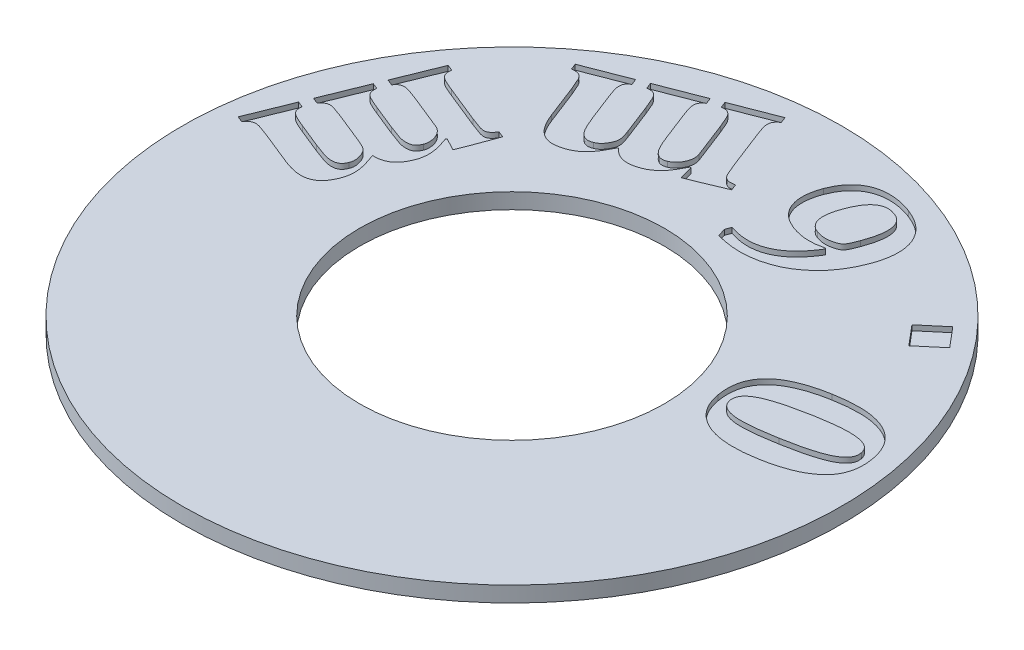
SolidWorks part; units mm, degrees
ref_plane "Front Plane" through (0, 0, 0) normal (0, 0, 1) x (1, 0, 0)
ref_plane "Top Plane" through (0, 0, 0) normal (0, 1, 0) x (1, 0, 0)
ref_plane "Right Plane" through (0, 0, 0) normal (1, 0, 0) x (0, 0, -1)
sketch "Sketch1" plane through (0, 0, 0) normal (0, 1, 0) x (1, 0, 0)
  circle A0 centre (0, 0) radius 12.7
  dimension "D1" = 25.4
extrude "Boss-Extrude1" add sketch "Sketch1" along normal blind 0.6
sketch "Sketch2" plane through (0, 0, 0) normal (0, -1, 0) x (-1, 0, 0)
  circle A0 centre (0, 0) radius 5.8674
  dimension "D1" = 11.7348
extrude "Cut-Extrude1" cut sketch "Sketch2" against normal through all
sketch "Sketch4" plane through (0, 0.6, 0) normal (0, 1, 0) x (1, 0, 0)
  circle A0 centre (0, 0) radius 12.0429 construction
  text T0 "<b>0.6mm</b>" font "Cambria" height 5.08
extrude "Cut-Extrude2" cut sketch "Sketch4" against normal blind 0.2
